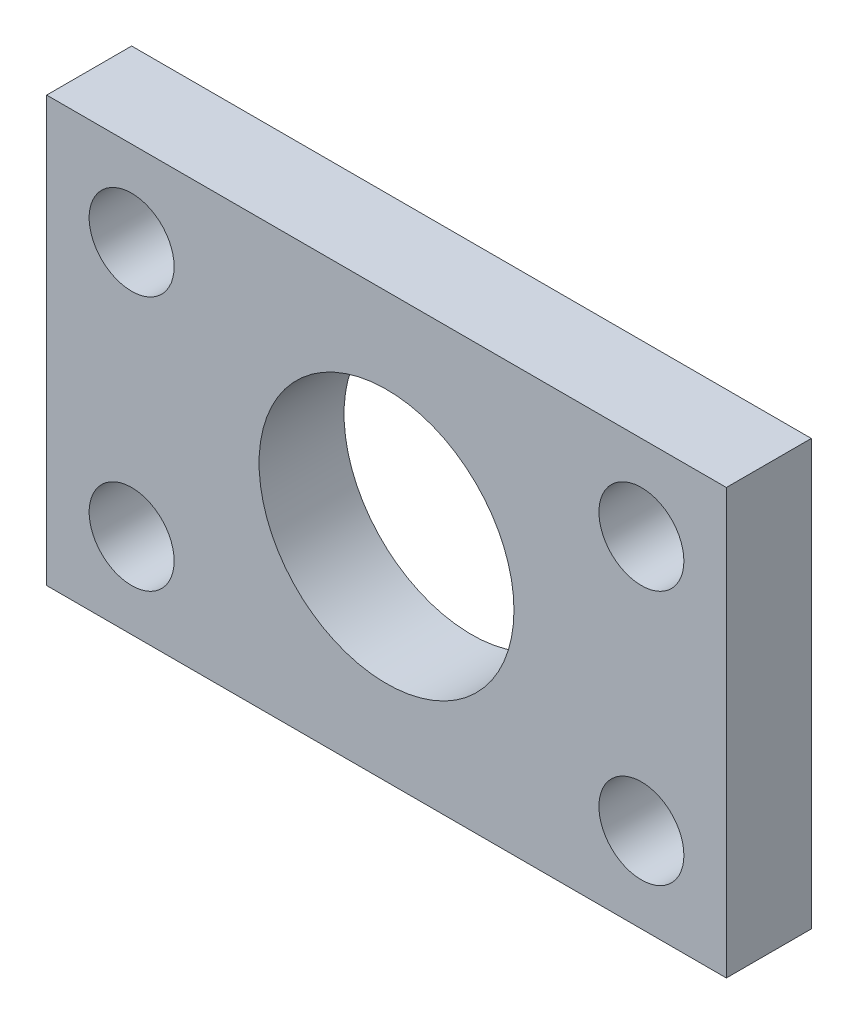
SolidWorks part; units mm, degrees
ref_plane "Front Plane" through (0, 0, 0) normal (0, 0, 1) x (1, 0, 0)
ref_plane "Top Plane" through (0, 0, 0) normal (0, 1, 0) x (1, 0, 0)
ref_plane "Right Plane" through (0, 0, 0) normal (1, 0, 0) x (0, 0, -1)
sketch "Sketch1" plane through (0, 0, 0) normal (0, 0, 1) x (1, 0, 0)
other "Pen Sketch1"
sketch "Sketch2" plane through (0, 0, 0) normal (0, 0, 1) x (1, 0, 0)
  line L0 (-76.2, 38.1) -> (76.2, 38.1) construction
  line L1 (-101.6, 63.5) -> (101.6, 63.5)
  line L2 (-101.6, 63.5) -> (-101.6, -63.5)
  line L3 (-101.6, -63.5) -> (101.6, -63.5)
  line L4 (101.6, 63.5) -> (101.6, -63.5)
  line L5 (76.2, 38.1) -> (76.2, -38.1) construction
  line L6 (-76.2, -38.1) -> (76.2, -38.1) construction
  line L7 (-76.2, 38.1) -> (-76.2, -38.1) construction
  line L8 (0, 63.5) -> (0, -63.5) construction
  circle A0 centre (-76.2, 38.1) radius 12.7
  circle A2 centre (76.2, -38.1) radius 12.7
  circle A3 centre (-76.2, -38.1) radius 12.7
  circle A4 centre (76.2, 38.1) radius 12.7
  circle A5 centre (0, 0) radius 38.1
  point P9 (0, 0)
  dimension "D4" = 25.4
  dimension "D5" = 76.2
  dimension "D1" = 203.2
  dimension "D2" = 127
  dimension "D3" = 25.4
extrude "Boss-Extrude1" add sketch "Sketch2" along normal blind 25.4
